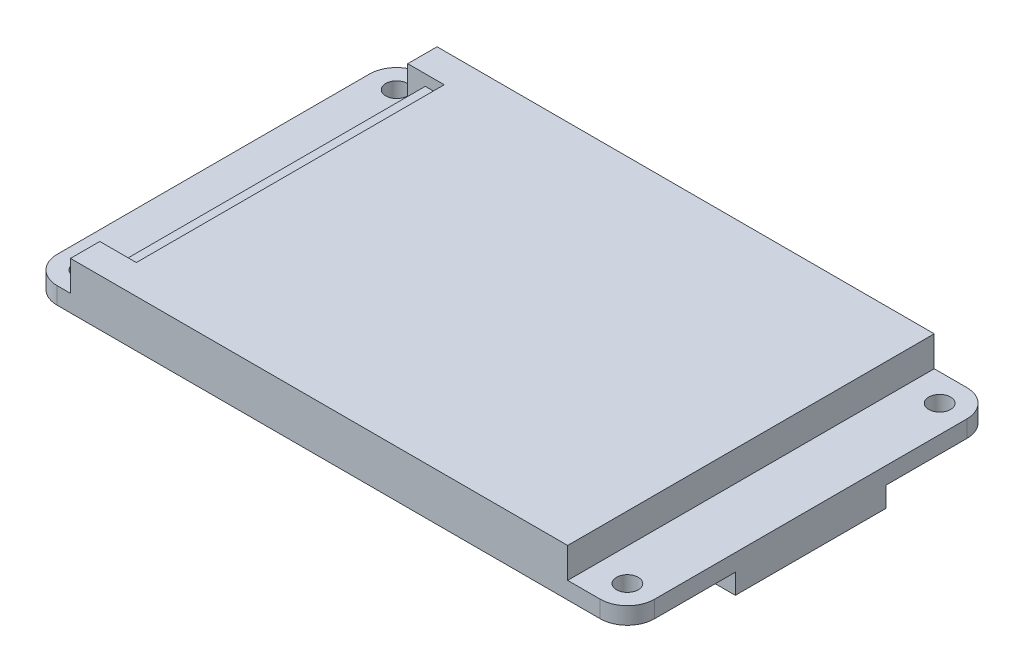
SolidWorks part; units mm, degrees
ref_plane "Front Plane" through (0, 0, 0) normal (0, 0, 1) x (1, 0, 0)
ref_plane "Top Plane" through (0, 0, 0) normal (0, 1, 0) x (1, 0, 0)
ref_plane "Right Plane" through (0, 0, 0) normal (1, 0, 0) x (0, 0, -1)
sketch "Sketch1" plane through (0, 0, 0) normal (0, 1, 0) x (1, 0, 0)
  line L1 (2.54, 0) -> (53.34, 0)
  line L2 (0, 2.54) -> (0, 31.75)
  line L3 (2.54, 34.29) -> (53.34, 34.29)
  line L4 (55.88, 2.54) -> (55.88, 31.75)
  arc A0 (53.34, 0) -> (55.88, 2.54) centre (53.34, 2.54) ccw
  arc A1 (53.34, 34.29) -> (55.88, 31.75) centre (53.34, 31.75) cw
  arc A2 (0, 31.75) -> (2.54, 34.29) centre (2.54, 31.75) cw
  arc A3 (2.54, 0) -> (0, 2.54) centre (2.54, 2.54) cw
  point P13 (0, 0)
  dimension "D1" = 2.54
  dimension "D2" = 55.88
  dimension "D3" = 34.29
extrude "Boss-Extrude1" add sketch "Sketch1" along normal blind 1.5875
sketch "Sketch2" plane through (0, 1.5875, 0) normal (0, 1, 0) x (1, 0, 0)
  line L0 (53.34, 34.29) -> (2.54, 34.29) construction
  line L1 (50.292, 34.29) -> (3.7846, 34.29)
  line L2 (50.292, 34.29) -> (50.292, 0)
  line L3 (50.292, 0) -> (3.7846, 0)
  line L4 (3.7846, 34.29) -> (3.7846, 31.5468)
  line L5 (2.54, 0) -> (53.34, 0) construction
  line L6 (55.88, 2.54) -> (55.88, 31.75) construction
  line L7 (3.7846, 2.7432) -> (3.7846, 0)
  line L8 (3.7846, 2.7432) -> (7.2009, 2.7432)
  line L10 (3.7846, 31.5468) -> (7.2009, 31.5468)
  line L11 (7.2009, 2.7432) -> (7.2009, 31.5468)
  dimension "D1" = 46.5074
  dimension "D2" = 5.588
  dimension "D3" = 28.8036
  dimension "D4" = 3.4163
extrude "Boss-Extrude2" add sketch "Sketch2" along normal offset from surface (2.8321 mm away) 4.4196 up to face at (27.94, 0, -17.145)
sketch "Sketch3" plane through (0, 1.5875, 0) normal (0, 1, 0) x (1, 0, 0)
  line L0 (7.2009, 31.5468) -> (7.2009, 2.7432) construction
  line L1 (5.4229, 31.5468) -> (7.2009, 31.5468)
  line L2 (5.4229, 31.5468) -> (5.4229, 2.7432)
  line L3 (5.4229, 2.7432) -> (7.2009, 2.7432)
  line L4 (7.2009, 31.5468) -> (7.2009, 2.7432)
  line L5 (3.7846, 31.5468) -> (7.2009, 31.5468) construction
  point P7 (7.2009, 2.7432)
  point P9 (4.8905, 31.5468)
  dimension "D1" = 1.778
extrude "Boss-Extrude3" add sketch "Sketch3" along normal offset from surface (1.8161 mm away) 1.016 up to face at (16.2655, 4.4196, -17.145)
sketch "Sketch4" plane through (0, 1.5875, 0) normal (0, 1, 0) x (1, 0, 0)
  circle A0 centre (2.54, 31.75) radius 1.016
  circle A1 centre (2.54, 2.54) radius 1.016
  circle A2 centre (53.34, 31.75) radius 1.016
  circle A3 centre (53.34, 2.54) radius 1.016
  arc A4 (55.88, 31.75) -> (53.34, 34.29) centre (53.34, 31.75) ccw construction
  arc A5 (2.54, 34.29) -> (0, 31.75) centre (2.54, 31.75) ccw construction
  arc A6 (0, 2.54) -> (2.54, 0) centre (2.54, 2.54) ccw construction
  arc A7 (53.34, 0) -> (55.88, 2.54) centre (53.34, 2.54) ccw construction
  dimension "D1" = 2.032
extrude "Cut-Extrude1" cut sketch "Sketch4" against normal through all
sketch "Sketch5" plane through (0, 0, 0) normal (0, -1, 0) x (1, 0, 0)
  line L0 (3.81, -29.845) -> (1.27, -27.305) construction
  line L1 (1.27, -29.845) -> (3.81, -29.845)
  line L2 (1.27, -29.845) -> (1.27, -4.445)
  line L3 (1.27, -4.445) -> (3.81, -4.445)
  line L4 (3.81, -29.845) -> (3.81, -4.445)
  line L5 (1.27, -27.305) -> (3.81, -27.305) construction
  line L6 (3.81, -4.445) -> (1.27, -6.985) construction
  line L7 (1.27, -6.985) -> (3.81, -6.985) construction
  line L8 (2.54, -27.305) -> (2.54, -29.845) construction
  line L9 (2.54, -6.985) -> (2.54, -4.445) construction
  line L10 (55.88, -2.54) -> (55.88, -31.75) construction
  line L11 (2.54, 0) -> (53.34, 0) construction
  point P12 (2.54, -28.575)
  point P13 (2.54, -5.715)
  dimension "D1" = 53.34
  dimension "D2" = 28.575
  dimension "D3" = 25.4
  dimension "D4" = 2.54
extrude "Boss-Extrude4" add sketch "Sketch5" along normal offset from surface (2.6289 mm away) 4.2164 up to face at (2.54, 1.5875, -1.524)
sketch "Sketch6" plane through (0, 0, 0) normal (0, -1, 0) x (1, 0, 0)
  line L0 (55.88, -2.54) -> (55.88, -31.75) construction
  line L1 (55.88, -24.1935) -> (39.3192, -24.1935)
  line L2 (55.88, -24.1935) -> (55.88, -10.0965)
  line L3 (55.88, -10.0965) -> (39.3192, -10.0965)
  line L4 (39.3192, -24.1935) -> (39.3192, -10.0965)
  point P6 (55.88, -17.145)
  point P7 (0, 0)
  dimension "D1" = 14.097
  dimension "D2" = 16.5608
extrude "Boss-Extrude5" add sketch "Sketch6" along normal blind 1.8796
